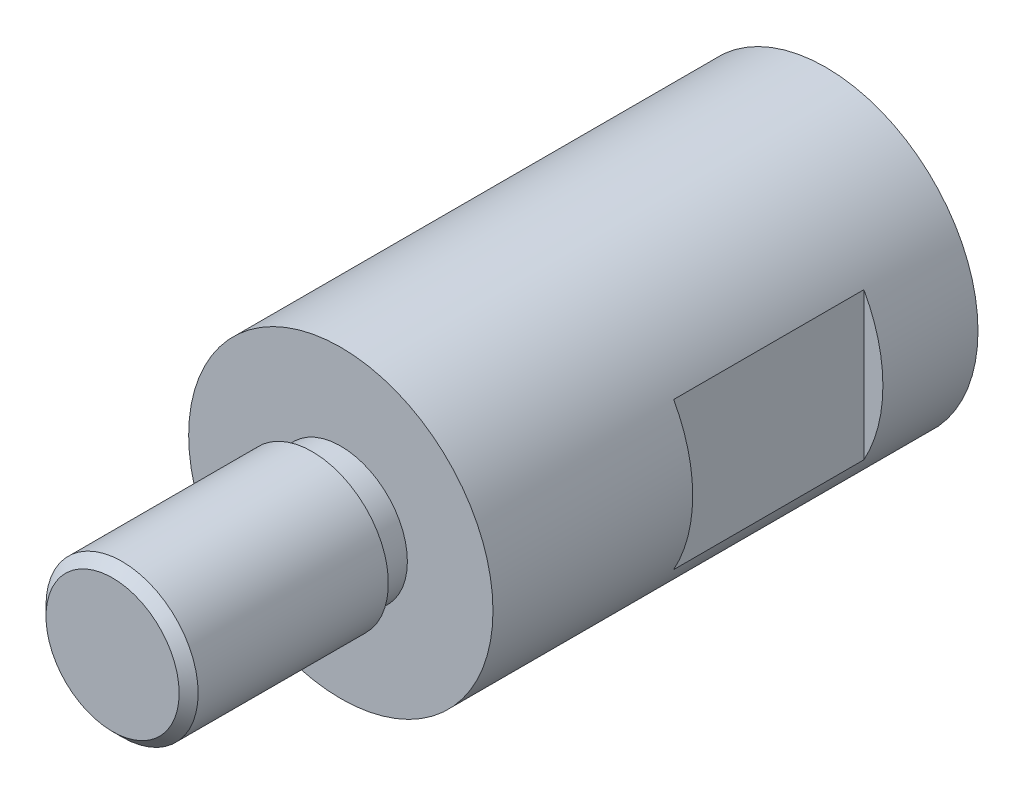
SolidWorks part; units mm, degrees
ref_plane "前视基准面" through (0, 0, 0) normal (0, 0, 1) x (1, 0, 0)
ref_plane "上视基准面" through (0, 0, 0) normal (0, 1, 0) x (1, 0, 0)
ref_plane "右视基准面" through (0, 0, 0) normal (1, 0, 0) x (0, 0, -1)
sketch "草图1" plane through (0, 0, 0) normal (0, 0, 1) x (1, 0, 0)
  circle A0 centre (0, 0) radius 8
  dimension "D1" = 16
extrude "拉伸1" add sketch "草图1" along normal blind 25.5
sketch "草图2" plane through (0, 0, 0) normal (0, 1, 0) x (1, 0, 0)
  line L0 (-8, 0) -> (-8, -25.5) construction
  line L1 (-8, -5) -> (-7, -5)
  line L2 (-8, -5) -> (-8, -15)
  line L3 (-8, -15) -> (-7, -15)
  line L4 (-7, -5) -> (-7, -15)
  line L5 (8, -25.5) -> (8, 0) construction
  line L6 (8, -5) -> (7, -5)
  line L7 (8, -5) -> (8, -15)
  line L8 (8, -15) -> (7, -15)
  line L9 (7, -5) -> (7, -15)
  line L10 (8, 0) -> (-8, 0) construction
  dimension "D1" = 10
  dimension "D2" = 10
  dimension "D3" = 14
  dimension "D4" = 1
  dimension "D5" = 5
  dimension "D6" = 5
extrude "拉伸2" cut sketch "草图2" against normal mid plane 18.5
hole_wizard "M8 螺纹孔1" positions "3D草图1" profile "草图3" tap size "M8" standard "GB"
sketch3d "3D草图1"
  point P1 (0, 0, 0)
sketch "草图3" plane through (0, 0, 0) normal (1, 0, 0) x (0, 1, 0)
  line L0 (0, 0) -> (0, 21.7929)
  line L1 (0, 21.7929) -> (3.4, 19.75)
  line L2 (3.4, 19.75) -> (3.4, 16)
  line L3 (3.4, 16) -> (4, 16)
  line L4 (4, 16) -> (4, 0)
  line L5 (4, 0) -> (0, 0)
  line L10 (0, 21.7929) -> (-3.4, 19.75) construction
  line L11 (0, -6.35) -> (0, 107.95) construction
  dimension "螺纹孔钻头直径" = 6.8
  dimension "螺纹孔钻头深度" = 19.75
  dimension "螺纹主直径" = 8
  dimension "螺纹深度" = 16
  dimension "导头角度" = 118
sketch "草图4" plane through (0, 0, 25.5) normal (0, 0, 1) x (1, 0, 0)
  circle A0 centre (0, 0) radius 4
  dimension "D1" = 8
extrude "拉伸3" add sketch "草图4" along normal blind 12
cosmetic thread "装饰螺纹线1" parameters "D1"=10.5, "D2"=6.8
chamfer "倒角1" distance 0.5 angle 45 1 edges at (4, 0, 37.5)
sketch "草图5" plane through (0, 0, 0) normal (1, 0, 0) x (0, 0, -1)
  line L0 (-25.5, 4) -> (-25.5, -4) construction
  line L1 (-25.5, 3.5) -> (-27, 3.5)
  line L2 (-25.5, 3.5) -> (-25.5, 4.43)
  line L3 (-25.5, 4.43) -> (-27, 4.43)
  line L4 (-27, 3.5) -> (-27, 4.43)
  line L5 (-25.5, 4) -> (-37, 4) construction
  dimension "D1" = 0.5
  dimension "D2" = 1.5
revolve "切除-旋转1" cut sketch "草图5" angle 360 about axis through (0, 0, 25.5) along (0, 0, -1)
